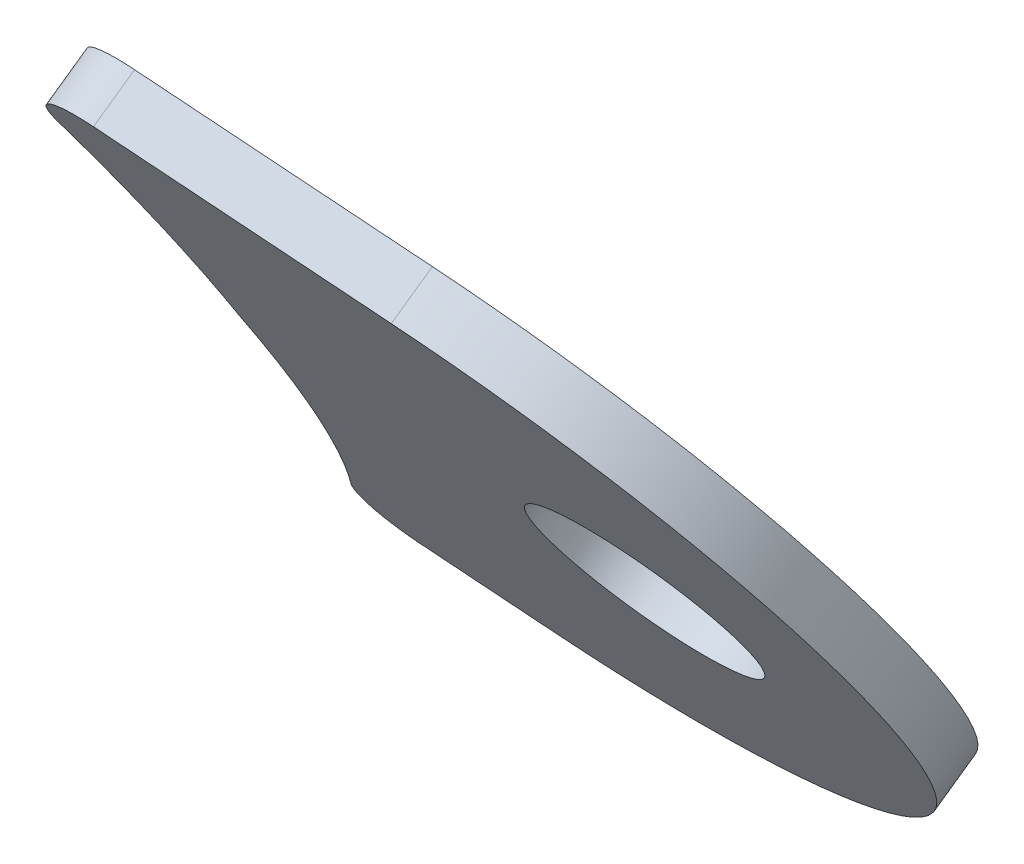
SolidWorks part; units mm, degrees
ref_plane "Front Plane" through (0, 0, 0) normal (0, 0, 1) x (1, 0, 0)
ref_plane "Top Plane" through (0, 0, 0) normal (0, 1, 0) x (1, 0, 0)
ref_plane "Right Plane" through (0, 0, 0) normal (1, 0, 0) x (0, 0, -1)
ref_plane "Plane1" through (0, 220.8127, -315.3533) normal (0, 0.5736, -0.8192) x (-1, 0, 0)
sketch "Sketch1" plane through (0, 220.8127, -315.3533) normal (0, 0.5736, -0.8192) x (-1, 0, 0)
  line L0 (-352.9369, 115.8265) -> (-375.2959, 107.875)
  line L1 (-366.7852, 83.9433) -> (-352.9369, 88.8681)
  line L2 (-352.9369, 88.8681) -> (-352.9369, 115.8265)
  line L3 (-371.0405, 95.9092) -> (-375.5277, 94.3134) construction
  arc A0 (-375.2959, 107.875) -> (-366.7852, 83.9433) centre (-371.0405, 95.9092) ccw
  circle A2 centre (-375.5277, 94.3134) radius 3.302
  point P5 (-352.9369, 102.3473)
  dimension "D1" = 25.4
  dimension "D2" = 4.7625
extrude "Boss-Extrude1" add sketch "Sketch1" along normal blind 1.5875
ref_plane "Plane2" through (364.3517, 343.6254, -135.3997) normal (-0.0893, -0.3048, -0.9482) x (-0.996, 0.0273, 0.085)
sketch "Sketch2" plane through (364.3517, 343.6254, -135.3997) normal (-0.0893, -0.3048, -0.9482) x (-0.996, 0.0273, 0.085)
  circle A0 centre (-0.0378, -0.5075) radius 12.7
  dimension "D1" = 25.4
extrude "Cut-Extrude2" cut sketch "Sketch2" along normal through all
sketch "Sketch3" plane through (0, 221.7233, -316.6537) normal (0, 0.5736, -0.8192) x (-1, 0, 0)
  line L0 (-361.4453, 85.8423) -> (-360.534, 86.1664)
  line L1 (-360.534, 86.1664) -> (-363.8042, 111.9618)
  ellipse E0 centre (-352.6795, 99.4145) end of major axis (-355.0381, 120.3816) minor radius 12.7 (-363.8042, 111.9618) -> (-361.4453, 85.8423) ccw construction
  ellipse E1 centre (-352.6795, 99.4145) end of major axis (-355.0381, 120.3816) minor radius 12.7 (-363.8042, 111.9618) -> (-361.4453, 85.8423) ccw
extrude "Cut-Extrude3" cut sketch "Sketch3" against normal through all
sketch "Sketch5" plane through (0, 220.8127, -315.3533) normal (0, -0.5736, 0.8192) x (1, 0, 0)
  line L1 (364.8196, 111.6006) -> (363.8042, 111.9618)
  line L2 (363.8042, 111.9618) -> (365.4018, 99.043)
  ellipse E1 centre (352.9149, 101.5074) end of major axis (355.2735, 122.4746) minor radius 12.7 (365.4018, 99.043) -> (364.8196, 111.6006) ccw construction
  ellipse E3 centre (352.9149, 101.5074) end of major axis (355.2735, 122.4746) minor radius 12.7 (365.4018, 99.043) -> (364.8196, 111.6006) ccw
extrude "Cut-Extrude4" cut sketch "Sketch5" against normal through all
fillet "Fillet1" radius 1.5875 2 edges at (361.4453, 291.5859, -266.7664) (364.8196, 312.6859, -251.992)
